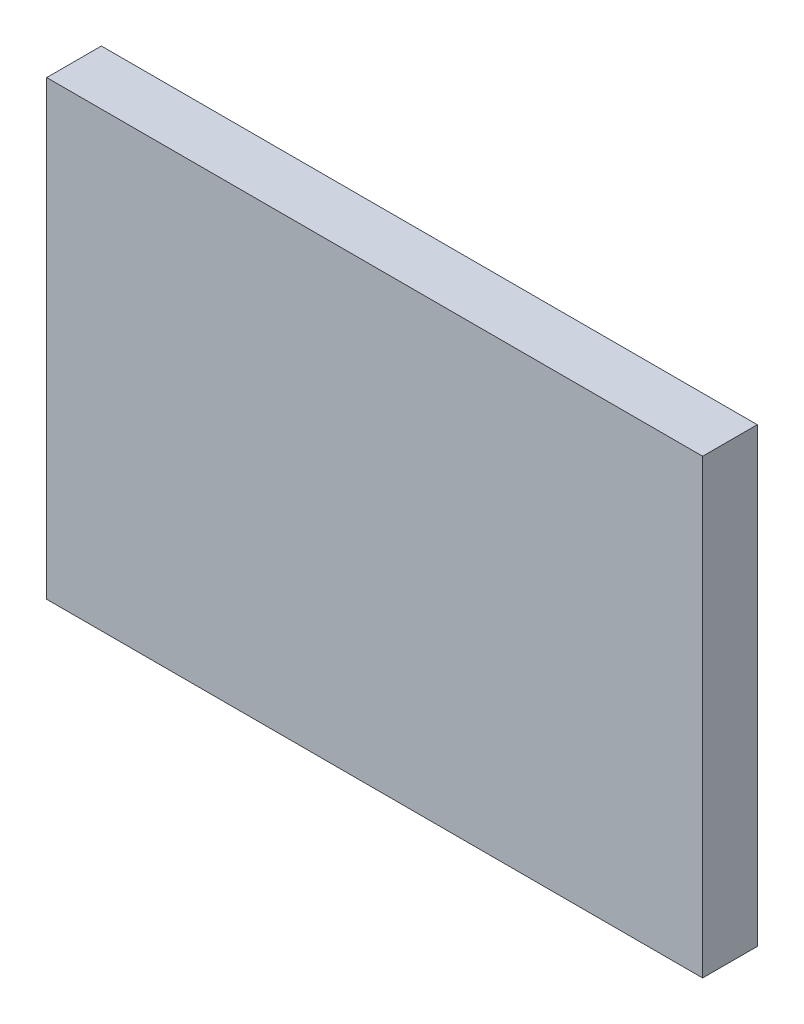
SolidWorks part; units mm, degrees
ref_plane "Front Plane" through (0, 0, 0) normal (0, 0, 1) x (1, 0, 0)
ref_plane "Top Plane" through (0, 0, 0) normal (0, 1, 0) x (1, 0, 0)
ref_plane "Right Plane" through (0, 0, 0) normal (1, 0, 0) x (0, 0, -1)
sketch "Sketch1" plane through (0, 0, 0) normal (0, 0, 1) x (1, 0, 0)
  line L1 (-22.86, -15.748) -> (22.86, -15.748)
  line L2 (-22.86, -15.748) -> (-22.86, 15.748)
  line L3 (-22.86, 15.748) -> (22.86, 15.748)
  line L4 (22.86, -15.748) -> (22.86, 15.748)
  line L5 (-22.86, -15.748) -> (22.86, 15.748) construction
  line L6 (-22.86, 15.748) -> (22.86, -15.748) construction
  point P0 (0, 0)
  dimension "D1" = 45.72
  dimension "D2" = 31.496
extrude "Boss-Extrude1" add sketch "Sketch1" along normal blind 3.81
